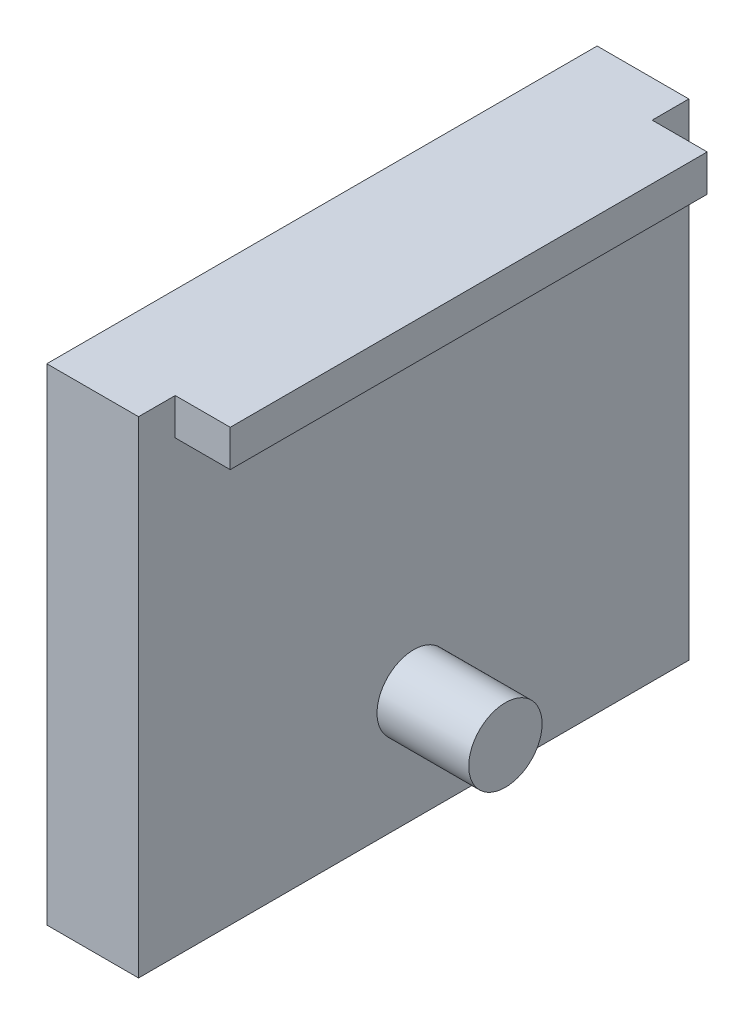
SolidWorks part; units mm, degrees
ref_plane "Front Plane" through (0, 0, 0) normal (0, 0, 1) x (1, 0, 0)
ref_plane "Top Plane" through (0, 0, 0) normal (0, 1, 0) x (1, 0, 0)
ref_plane "Right Plane" through (0, 0, 0) normal (1, 0, 0) x (0, 0, -1)
ref_plane "Plane1" through (-179.1508, 0, 0) normal (1, 0, 0) x (0, 0, -1)
sketch "Sketch1" plane through (-179.1508, 0, 0) normal (1, 0, 0) x (0, 0, -1)
  line L0 (-134, 37) -> (-134, 63.5)
  line L1 (-134, 63.5) -> (-164, 63.5)
  line L2 (-164, 63.5) -> (-164, 37)
  line L3 (-164, 37) -> (-134, 37)
extrude "Boss-Extrude1" add sketch "Sketch1" along normal mid plane 5
ref_plane "Plane2" through (-181.6508, 0, 0) normal (1, 0, 0) x (0, 0, -1)
sketch "Sketch2" plane through (-181.6508, 0, 0) normal (1, 0, 0) x (0, 0, -1)
  line L0 (-138, 40) -> (-138, 42)
  line L1 (-138, 42) -> (-160, 42)
  line L2 (-160, 42) -> (-160, 40)
  line L3 (-160, 40) -> (-138, 40)
  line L4 (-138, 44) -> (-138, 46)
  line L5 (-138, 46) -> (-160, 46)
  line L6 (-160, 46) -> (-160, 44)
  line L7 (-160, 44) -> (-138, 44)
extrude "Boss-Extrude2" add sketch "Sketch2" along normal mid plane 1
ref_plane "Plane3" through (-175.1508, 0, 0) normal (1, 0, 0) x (0, 0, -1)
sketch "Sketch3" plane through (-175.1508, 0, 0) normal (1, 0, 0) x (0, 0, -1)
  line L0 (-136, 61.5) -> (-136, 63.5)
  line L1 (-136, 63.5) -> (-162, 63.5)
  line L2 (-162, 63.5) -> (-162, 61.5)
  line L3 (-162, 61.5) -> (-136, 61.5)
extrude "Boss-Extrude3" add sketch "Sketch3" along normal mid plane 3
ref_plane "Plane4" through (-174.1508, 0, 0) normal (1, 0, 0) x (0, 0, -1)
sketch "Sketch4" plane through (-174.1508, 0, 0) normal (1, 0, 0) x (0, 0, -1)
  circle A0 centre (-149, 43) radius 2
extrude "Boss-Extrude4" add sketch "Sketch4" along normal mid plane 5
